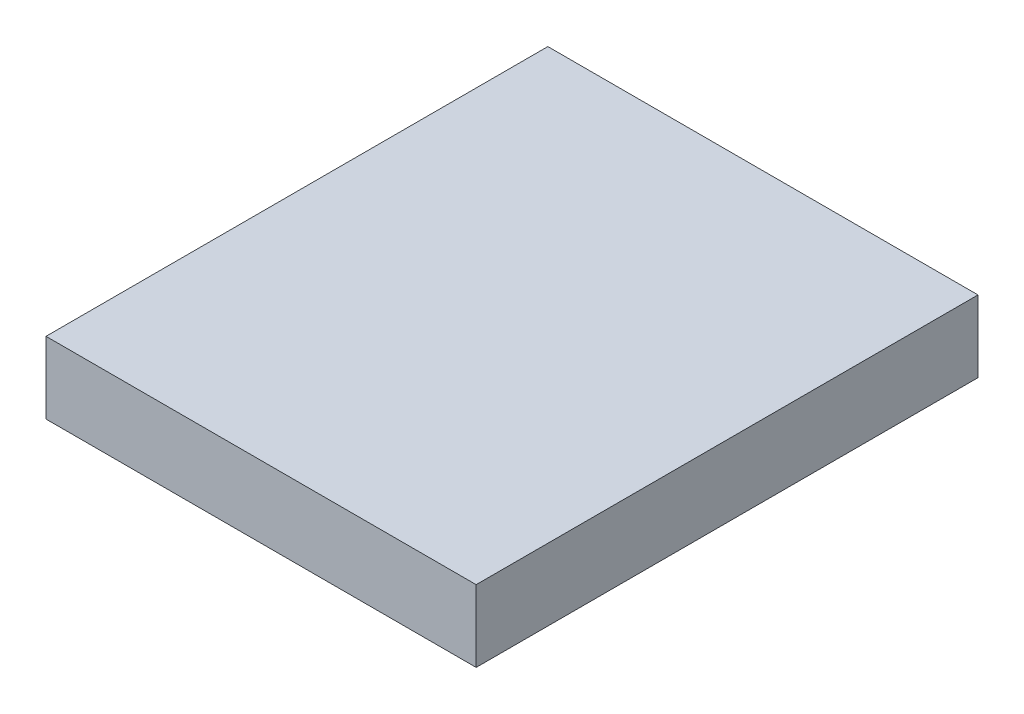
SolidWorks part; units mm, degrees
ref_plane "Front Plane" through (0, 0, 0) normal (0, 0, 1) x (1, 0, 0)
ref_plane "Top Plane" through (0, 0, 0) normal (0, 1, 0) x (1, 0, 0)
ref_plane "Right Plane" through (0, 0, 0) normal (1, 0, 0) x (0, 0, -1)
sketch "Sketch1" plane through (0, 0, 0) normal (0, 1, 0) x (1, 0, 0)
  line L1 (-228.6, -266.7) -> (228.6, -266.7)
  line L2 (-228.6, -266.7) -> (-228.6, 266.7)
  line L3 (-228.6, 266.7) -> (228.6, 266.7)
  line L4 (228.6, -266.7) -> (228.6, 266.7)
  line L5 (-228.6, -266.7) -> (228.6, 266.7) construction
  line L6 (-228.6, 266.7) -> (228.6, -266.7) construction
  point P0 (0, 0)
  dimension "D1" = 457.2
  dimension "D2" = 533.4
extrude "Boss-Extrude1" add sketch "Sketch1" along normal blind 76.2
